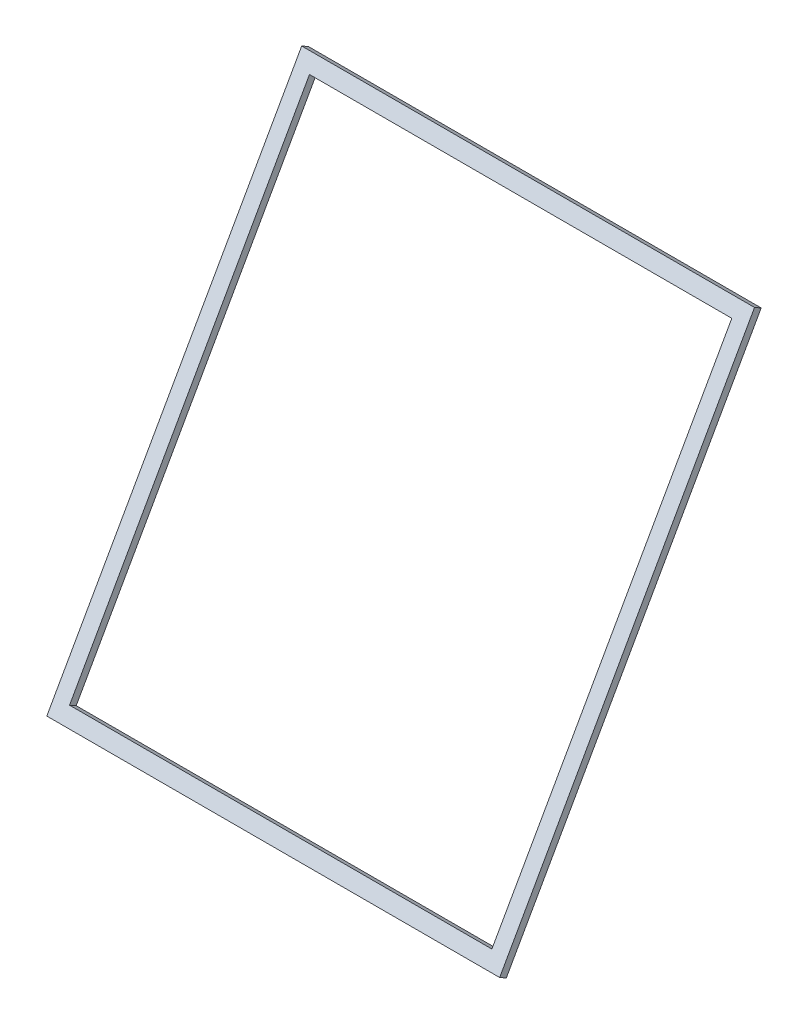
SolidWorks part; units mm, degrees
ref_plane "Alzado" through (0, 0, 0) normal (0, 0, 1) x (1, 0, 0)
ref_plane "Planta" through (0, 0, 0) normal (0, 1, 0) x (1, 0, 0)
ref_plane "Vista lateral" through (0, 0, 0) normal (1, 0, 0) x (0, 0, -1)
ref_plane "Plano1" through (0, 37.5761, 66.7597) normal (0, -0.4905, -0.8714) x (-1, 0, 0)
sketch "Croquis2" plane through (0, 37.5761, 66.7597) normal (0, -0.4905, -0.8714) x (-1, 0, 0)
  line L0 (7.7541, 166.6871) -> (7.7541, -163.3633) construction
  line L1 (-149.7459, 166.6871) -> (165.2541, 166.6871) construction
  line L2 (-130.6395, 139.4235) -> (146.1477, 139.4235)
  line L3 (-140.6395, 149.4235) -> (156.1477, 149.4235)
  line L4 (-140.6395, 149.4235) -> (-140.6395, -191.1467)
  line L5 (-140.6395, -191.1467) -> (156.1477, -191.1467)
  line L6 (156.1477, 149.4235) -> (156.1477, -191.1467)
  line L7 (-140.6395, 149.4235) -> (156.1477, -191.1467) construction
  line L8 (-140.6395, -191.1467) -> (156.1477, 149.4235) construction
  line L9 (146.1477, 139.4235) -> (146.1477, -181.1467)
  line L10 (-130.6395, -181.1467) -> (146.1477, -181.1467)
  line L11 (-130.6395, 139.4235) -> (-130.6395, -181.1467)
  point P4 (7.7541, -20.8616)
  dimension "D1" = 10
extrude "Saliente-Extruir1" add sketch "Croquis2" against normal blind 5
